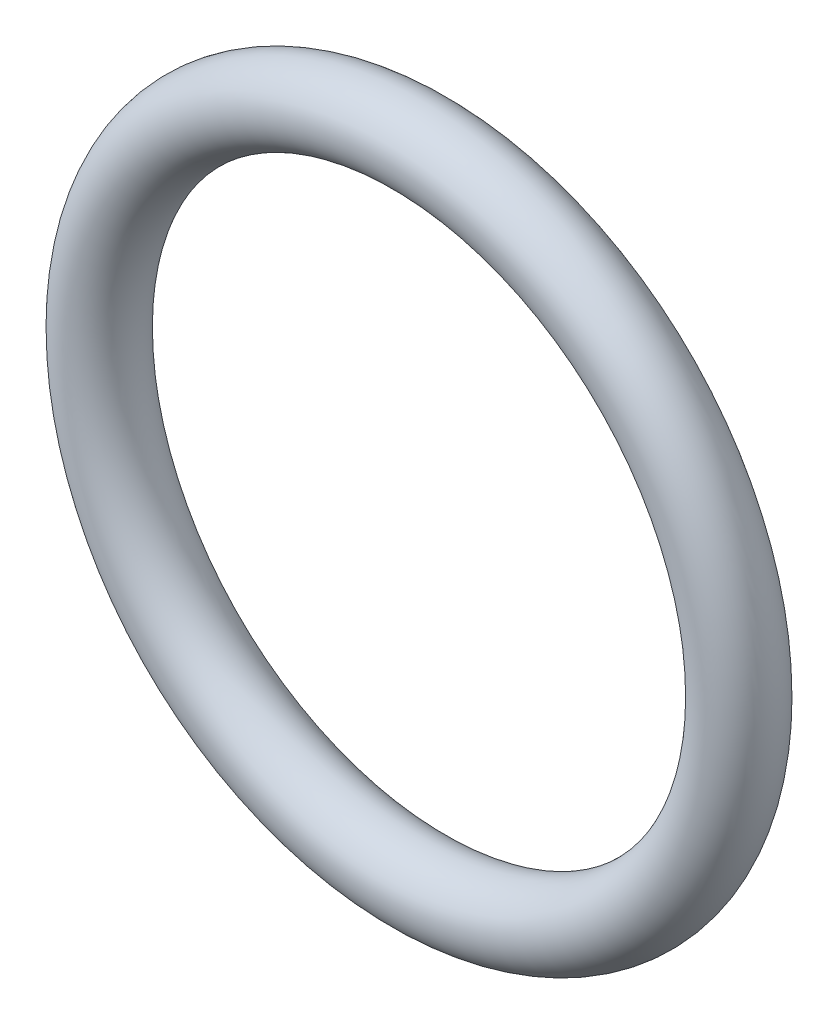
SolidWorks part; units mm, degrees
ref_plane "Front Plane" through (0, 0, 0) normal (0, 0, 1) x (1, 0, 0)
ref_plane "Top Plane" through (0, 0, 0) normal (0, 1, 0) x (1, 0, 0)
ref_plane "Right Plane" through (0, 0, 0) normal (1, 0, 0) x (0, 0, -1)
sketch "Sketch1" plane through (0, 0, 0) normal (0, 0, 1) x (1, 0, 0)
  circle A0 centre (0, 0) radius 21.25
  dimension "D1" = 42.5
sweep "Sweep1" add path "Sketch1" circular profile diameter 5 parameters "D3"=5
